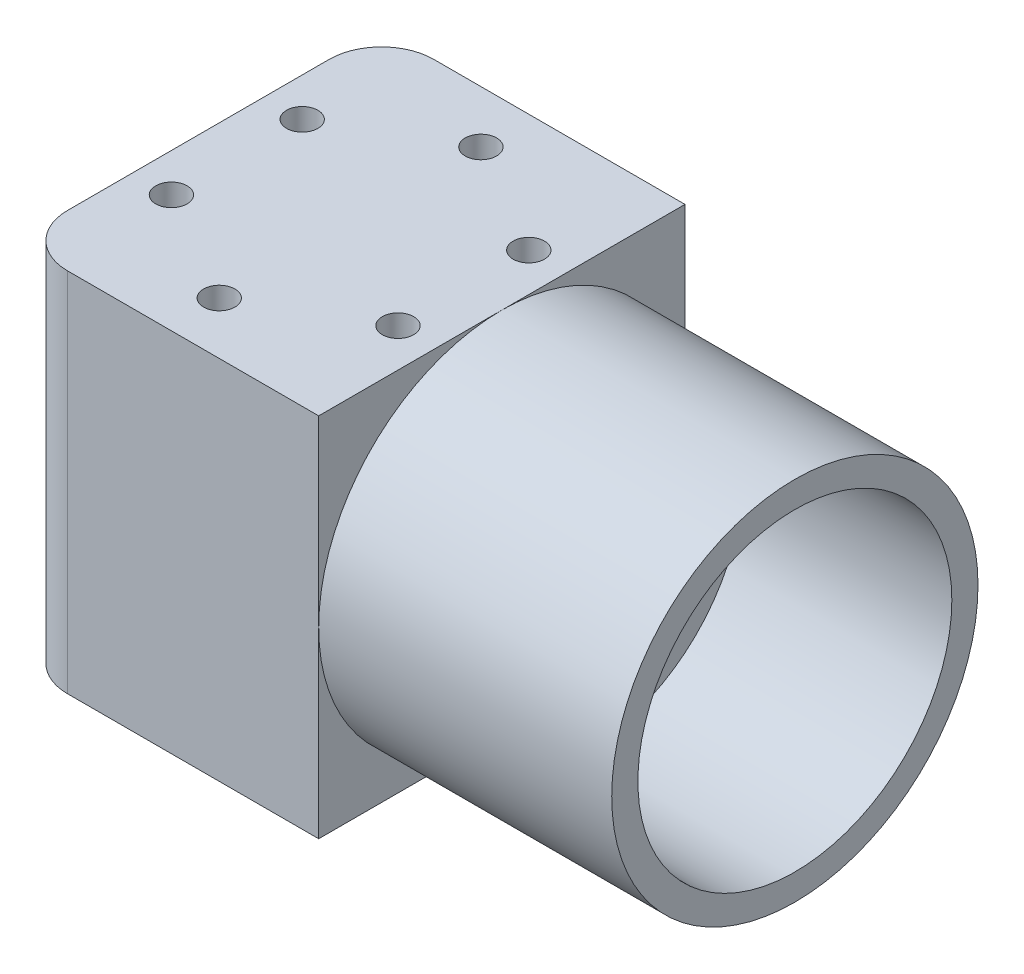
SolidWorks part; units mm, degrees
material "3.3547 (EN-AW 5083)"
ref_plane "Front Plane" through (0, 0, 0) normal (0, 0, 1) x (1, 0, 0)
ref_plane "Top Plane" through (0, 0, 0) normal (0, 1, 0) x (1, 0, 0)
ref_plane "Right Plane" through (0, 0, 0) normal (1, 0, 0) x (0, 0, -1)
sketch "Sketch1" plane through (0, 0, 0) normal (0, 1, 0) x (1, 0, 0)
  line L1 (-14.5, -17.5) -> (14.5, -17.5)
  line L2 (-14.5, -17.5) -> (-14.5, 17.5)
  line L3 (-14.5, 17.5) -> (14.5, 17.5)
  line L4 (14.5, -17.5) -> (14.5, 17.5)
  line L5 (-14.5, -17.5) -> (14.5, 17.5) construction
  line L6 (-14.5, 17.5) -> (14.5, -17.5) construction
  point P0 (0, 0)
  dimension "D1" = 35
  dimension "D2" = 29
extrude "Boss-Extrude1" add sketch "Sketch1" along normal mid plane 35
fillet "Fillet1" radius 5 2 edges at (-14.5, 0, -17.5) (-14.5, 0, 17.5)
sketch "Sketch2" plane through (14.5, 0, 0) normal (1, 0, 0) x (0, 0, -1)
  circle A0 centre (0, 0) radius 17.5
  dimension "D1" = 35
extrude "Boss-Extrude2" add sketch "Sketch2" along normal blind 28
sketch "Sketch3" plane through (42.5, 0, 0) normal (1, 0, 0) x (0, 0, -1)
  circle A0 centre (0, 0) radius 15
  dimension "D1" = 30
extrude "Cut-Extrude1" cut sketch "Sketch3" against normal blind 20
sketch "Sketch4" plane through (0, -17.5, 0) normal (0, -1, 0) x (1, 0, 0)
  line L0 (0, -44.7868) -> (0, 44.7868) construction
  circle A0 centre (0, 12.5) radius 1.5
  circle A1 centre (10.8253, 6.25) radius 1.5
  circle A2 centre (10.8253, -6.25) radius 1.5
  circle A3 centre (0, -12.5) radius 1.5
  circle A4 centre (-10.8253, -6.25) radius 1.5
  circle A5 centre (-10.8253, 6.25) radius 1.5
  point P17 (0, 0)
  dimension "D1" = 3
  dimension "D2" = 12.5
  dimension "D3" = 6
extrude "Cut-Extrude2" cut sketch "Sketch4" against normal up to next
